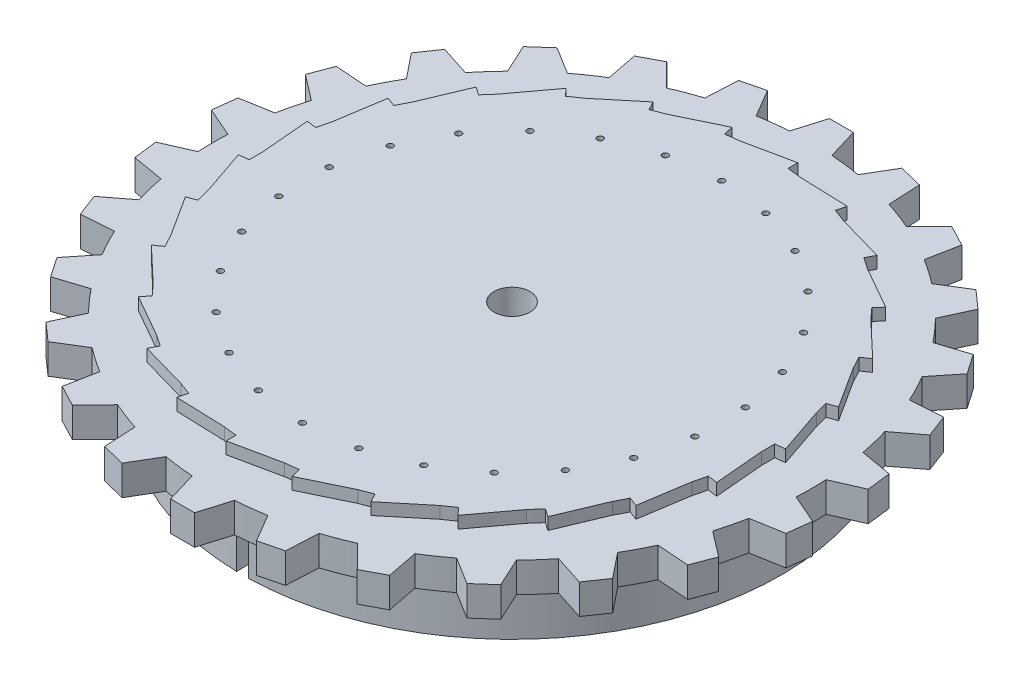
SolidWorks part; units mm, degrees
ref_plane "Front Plane" through (0, 0, 0) normal (0, 0, 1) x (1, 0, 0)
ref_plane "Top Plane" through (0, 0, 0) normal (0, 1, 0) x (1, 0, 0)
ref_plane "Right Plane" through (0, 0, 0) normal (1, 0, 0) x (0, 0, -1)
sketch "Gear sketch" plane through (0, 0, 0) normal (0, 1, 0) x (1, 0, 0)
  line L0 (0, 50) -> (-37.4438, 50) construction
  line L1 (3.5, 50) -> (-3.5, 50) construction
  line L2 (-3.5, 50) -> (-2, 55)
  line L3 (-2, 55) -> (2, 55)
  line L4 (2, 55) -> (3.5, 50)
  line L5 (0, 0) -> (0, 66.1206) construction
  line L6 (8.5675, 49.3847) -> (11.2205, 53.8804)
  line L7 (11.2205, 53.8804) -> (15.1042, 52.9232)
  line L8 (15.1042, 52.9232) -> (15.3641, 47.7095)
  line L9 (15.3641, 47.7095) -> (15.3706, 47.5788)
  line L10 (11.2205, 53.8804) -> (8.501, 49.272)
  line L11 (15.3641, 47.7095) -> (8.5675, 49.3847) construction
  line L12 (20.1371, 45.8993) -> (23.7889, 49.6295)
  line L13 (23.7889, 49.6295) -> (27.3307, 47.7706)
  line L14 (27.3307, 47.7706) -> (26.3353, 42.6463)
  line L15 (26.3353, 42.6463) -> (26.3103, 42.5179)
  line L16 (20.1371, 45.8993) -> (20.0455, 45.8059)
  line L18 (30.5363, 39.7465) -> (34.9747, 42.4943)
  line L19 (34.9747, 42.4943) -> (37.9688, 39.8418)
  line L20 (37.9688, 39.8418) -> (35.7759, 35.1046)
  line L21 (35.7759, 35.1046) -> (35.721, 34.9859)
  line L22 (30.5363, 39.7465) -> (30.4251, 39.6776)
  line L24 (39.161, 31.2837) -> (44.128, 32.8895)
  line L25 (44.128, 32.8895) -> (46.4002, 29.5976)
  line L26 (46.4002, 29.5976) -> (43.1374, 25.5228)
  line L27 (43.1374, 25.5228) -> (43.0557, 25.4207)
  line L28 (39.161, 31.2837) -> (39.0365, 31.2434)
  line L30 (45.5097, 21.0028) -> (50.7167, 21.3733)
  line L31 (50.7167, 21.3733) -> (52.1351, 17.6332)
  line L32 (52.1351, 17.6332) -> (47.9919, 14.4577)
  line L33 (47.9919, 14.4577) -> (47.8881, 14.3781)
  line L34 (45.5097, 21.0028) -> (45.3792, 20.9935)
  line L36 (49.2136, 9.5013) -> (54.3579, 8.6149)
  line L37 (54.3579, 8.6149) -> (54.8401, 4.6441)
  line L38 (54.8401, 4.6441) -> (50.0573, 2.5524)
  line L39 (50.0573, 2.5524) -> (49.9375, 2.4999)
  line L40 (49.2136, 9.5013) -> (49.0846, 9.5235)
  line L42 (50.0573, -2.5524) -> (54.8401, -4.6441)
  line L43 (54.8401, -4.6441) -> (54.3579, -8.6149)
  line L44 (54.3579, -8.6149) -> (49.2136, -9.5013)
  line L45 (49.2136, -9.5013) -> (49.0846, -9.5235)
  line L46 (50.0573, -2.5524) -> (49.9375, -2.4999)
  line L47 (49.2136, -9.5013) -> (50.0573, -2.5524) construction
  line L48 (47.9919, -14.4577) -> (52.1351, -17.6332)
  line L49 (52.1351, -17.6332) -> (50.7167, -21.3733)
  line L50 (50.7167, -21.3733) -> (45.5097, -21.0028)
  line L51 (45.5097, -21.0028) -> (45.3792, -20.9935)
  line L52 (47.9919, -14.4577) -> (47.8881, -14.3781)
  line L54 (43.1374, -25.5228) -> (46.4002, -29.5976)
  line L55 (46.4002, -29.5976) -> (44.128, -32.8895)
  line L56 (44.128, -32.8895) -> (39.161, -31.2837)
  line L57 (39.161, -31.2837) -> (39.0365, -31.2434)
  line L58 (43.1374, -25.5228) -> (43.0557, -25.4207)
  line L60 (35.7759, -35.1046) -> (37.9688, -39.8418)
  line L61 (37.9688, -39.8418) -> (34.9747, -42.4943)
  line L62 (34.9747, -42.4943) -> (30.5363, -39.7465)
  line L63 (30.5363, -39.7465) -> (30.4251, -39.6776)
  line L64 (35.7759, -35.1046) -> (35.721, -34.9859)
  line L66 (26.3353, -42.6463) -> (27.3307, -47.7706)
  line L67 (27.3307, -47.7706) -> (23.7889, -49.6295)
  line L68 (23.7889, -49.6295) -> (20.1371, -45.8993)
  line L69 (20.1371, -45.8993) -> (20.0455, -45.8059)
  line L70 (26.3353, -42.6463) -> (26.3103, -42.5179)
  line L72 (15.3641, -47.7095) -> (15.1042, -52.9232)
  line L73 (15.1042, -52.9232) -> (11.2205, -53.8804)
  line L74 (11.2205, -53.8804) -> (8.5675, -49.3847)
  line L75 (8.5675, -49.3847) -> (8.501, -49.272)
  line L76 (15.3641, -47.7095) -> (15.3706, -47.5788)
  line L78 (3.5, -50) -> (2, -55)
  line L79 (2, -55) -> (-2, -55)
  line L80 (-2, -55) -> (-3.5, -50)
  line L81 (3.5, 50) -> (3.5376, 49.8747)
  line L82 (-3.5, 50) -> (-3.5376, 49.8747)
  line L83 (-3.5, -50) -> (-3.5376, -49.8747)
  line L84 (3.5, -50) -> (3.5376, -49.8747)
  line L86 (-8.5675, -49.3847) -> (-11.2205, -53.8804)
  line L87 (-11.2205, -53.8804) -> (-15.1042, -52.9232)
  line L88 (-15.1042, -52.9232) -> (-15.3641, -47.7095)
  line L89 (-15.3641, -47.7095) -> (-15.3706, -47.5788)
  line L90 (-8.5675, -49.3847) -> (-8.501, -49.272)
  line L92 (-20.1371, -45.8993) -> (-23.7889, -49.6295)
  line L93 (-23.7889, -49.6295) -> (-27.3307, -47.7706)
  line L94 (-27.3307, -47.7706) -> (-26.3353, -42.6463)
  line L95 (-26.3353, -42.6463) -> (-26.3103, -42.5179)
  line L96 (-20.1371, -45.8993) -> (-20.0455, -45.8059)
  line L98 (-30.5363, -39.7465) -> (-34.9747, -42.4943)
  line L99 (-34.9747, -42.4943) -> (-37.9688, -39.8418)
  line L100 (-37.9688, -39.8418) -> (-35.7759, -35.1046)
  line L101 (-35.7759, -35.1046) -> (-35.721, -34.9859)
  line L102 (-30.5363, -39.7465) -> (-30.4251, -39.6776)
  line L104 (-39.161, -31.2837) -> (-44.128, -32.8895)
  line L105 (-44.128, -32.8895) -> (-46.4002, -29.5976)
  line L106 (-46.4002, -29.5976) -> (-43.1374, -25.5228)
  line L107 (-43.1374, -25.5228) -> (-43.0557, -25.4207)
  line L108 (-39.161, -31.2837) -> (-39.0365, -31.2434)
  line L110 (-45.5097, -21.0028) -> (-50.7167, -21.3733)
  line L111 (-50.7167, -21.3733) -> (-52.1351, -17.6332)
  line L112 (-52.1351, -17.6332) -> (-47.9919, -14.4577)
  line L113 (-47.9919, -14.4577) -> (-47.8881, -14.3781)
  line L114 (-45.5097, -21.0028) -> (-45.3792, -20.9935)
  line L116 (-49.2136, -9.5013) -> (-54.3579, -8.6149)
  line L117 (-54.3579, -8.6149) -> (-54.8401, -4.6441)
  line L118 (-54.8401, -4.6441) -> (-50.0573, -2.5524)
  line L119 (-50.0573, -2.5524) -> (-49.9375, -2.4999)
  line L120 (-49.2136, -9.5013) -> (-49.0846, -9.5235)
  line L122 (-50.0573, 2.5524) -> (-54.8401, 4.6441)
  line L123 (-54.8401, 4.6441) -> (-54.3579, 8.6149)
  line L124 (-54.3579, 8.6149) -> (-49.2136, 9.5013)
  line L125 (-49.2136, 9.5013) -> (-49.0846, 9.5235)
  line L126 (-50.0573, 2.5524) -> (-49.9375, 2.4999)
  line L128 (-47.9919, 14.4577) -> (-52.1351, 17.6332)
  line L129 (-52.1351, 17.6332) -> (-50.7167, 21.3733)
  line L130 (-50.7167, 21.3733) -> (-45.5097, 21.0028)
  line L131 (-45.5097, 21.0028) -> (-45.3792, 20.9935)
  line L132 (-47.9919, 14.4577) -> (-47.8881, 14.3781)
  line L134 (-43.1374, 25.5228) -> (-46.4002, 29.5976)
  line L135 (-46.4002, 29.5976) -> (-44.128, 32.8895)
  line L136 (-44.128, 32.8895) -> (-39.161, 31.2837)
  line L137 (-39.161, 31.2837) -> (-39.0365, 31.2434)
  line L138 (-43.1374, 25.5228) -> (-43.0557, 25.4207)
  line L140 (-35.7759, 35.1046) -> (-37.9688, 39.8418)
  line L141 (-37.9688, 39.8418) -> (-34.9747, 42.4943)
  line L142 (-34.9747, 42.4943) -> (-30.5363, 39.7465)
  line L143 (-30.5363, 39.7465) -> (-30.4251, 39.6776)
  line L144 (-35.7759, 35.1046) -> (-35.721, 34.9859)
  line L145 (-30.5363, 39.7465) -> (-35.7759, 35.1046) construction
  line L146 (-26.3353, 42.6463) -> (-27.3307, 47.7706)
  line L147 (-27.3307, 47.7706) -> (-23.7889, 49.6295)
  line L148 (-23.7889, 49.6295) -> (-20.1371, 45.8993)
  line L149 (-20.1371, 45.8993) -> (-20.0455, 45.8059)
  line L150 (-26.3353, 42.6463) -> (-26.3103, 42.5179)
  line L151 (-20.1371, 45.8993) -> (-23.2362, 44.2728) construction
  line L152 (-15.3641, 47.7095) -> (-15.1042, 52.9232)
  line L153 (-15.1042, 52.9232) -> (-11.2205, 53.8804)
  line L154 (-11.2205, 53.8804) -> (-8.5675, 49.3847)
  line L155 (-8.5675, 49.3847) -> (-8.501, 49.272)
  line L156 (-15.3641, 47.7095) -> (-15.3706, 47.5788)
  line L159 (49.6354, 6.0268) -> (49.2136, 9.5013) construction
  line L160 (47.9919, 14.4577) -> (45.5097, 21.0028) construction
  line L161 (43.1374, 25.5228) -> (39.161, 31.2837) construction
  line L162 (35.7759, 35.1046) -> (30.5363, 39.7465) construction
  line L163 (26.3353, 42.6463) -> (20.1371, 45.8993) construction
  line L164 (45.5097, -21.0028) -> (47.9919, -14.4577) construction
  line L165 (39.161, -31.2837) -> (41.1492, -28.4032) construction
  line L166 (30.5363, -39.7465) -> (35.7759, -35.1046) construction
  line L167 (20.1371, -45.8993) -> (23.2362, -44.2728) construction
  line L168 (11.9658, -48.5471) -> (15.3641, -47.7095) construction
  line L169 (-3.5, -50) -> (0, -50) construction
  line L170 (-15.3641, -47.7095) -> (-8.5675, -49.3847) construction
  line L171 (-26.3353, -42.6463) -> (-23.2362, -44.2728) construction
  line L172 (-33.1561, -37.4255) -> (-30.5363, -39.7465) construction
  line L173 (-41.1492, -28.4032) -> (-39.161, -31.2837) construction
  line L174 (-46.7508, -17.7302) -> (-45.5097, -21.0028) construction
  line L175 (-49.6354, -6.0268) -> (-49.2136, -9.5013) construction
  line L176 (-49.2136, 9.5013) -> (-49.6354, 6.0268) construction
  line L177 (-45.5097, 21.0028) -> (-46.7508, 17.7302) construction
  line L178 (-39.161, 31.2837) -> (-41.1492, 28.4032) construction
  line L179 (-8.5675, 49.3847) -> (-15.3641, 47.7095) construction
  arc A0 (-3.5376, 49.8747) -> (-8.501, 49.272) centre (0, 0) ccw
  arc A1 (8.501, 49.272) -> (3.5376, 49.8747) centre (0, 0) ccw
  arc A2 (20.0455, 45.8059) -> (15.3706, 47.5788) centre (0, 0) ccw
  arc A3 (30.4251, 39.6776) -> (26.3103, 42.5179) centre (0, 0) ccw
  arc A4 (39.0365, 31.2434) -> (35.721, 34.9859) centre (0, 0) ccw
  arc A5 (45.3792, 20.9935) -> (43.0557, 25.4207) centre (0, 0) ccw
  arc A6 (49.9375, -2.4999) -> (49.9375, 2.4999) centre (0, 0) ccw
  arc A7 (49.0846, 9.5235) -> (47.8881, 14.3781) centre (0, 0) ccw
  arc A8 (47.8881, -14.3781) -> (49.0846, -9.5235) centre (0, 0) ccw
  arc A9 (43.0557, -25.4207) -> (45.3792, -20.9935) centre (0, 0) ccw
  arc A10 (35.721, -34.9859) -> (39.0365, -31.2434) centre (0, 0) ccw
  arc A11 (26.3103, -42.5179) -> (30.4251, -39.6776) centre (0, 0) ccw
  arc A12 (15.3706, -47.5788) -> (20.0455, -45.8059) centre (0, 0) ccw
  arc A13 (3.5376, -49.8747) -> (8.501, -49.272) centre (0, 0) ccw
  arc A14 (-8.501, -49.272) -> (-3.5376, -49.8747) centre (0, 0) ccw
  arc A15 (-20.0455, -45.8059) -> (-15.3706, -47.5788) centre (0, 0) ccw
  arc A16 (-30.4251, -39.6776) -> (-26.3103, -42.5179) centre (0, 0) ccw
  arc A17 (-39.0365, -31.2434) -> (-35.721, -34.9859) centre (0, 0) ccw
  arc A18 (-45.3792, -20.9935) -> (-43.0557, -25.4207) centre (0, 0) ccw
  arc A19 (-49.0846, -9.5235) -> (-47.8881, -14.3781) centre (0, 0) ccw
  arc A20 (-49.9375, 2.4999) -> (-49.9375, -2.4999) centre (0, 0) ccw
  arc A21 (-47.8881, 14.3781) -> (-49.0846, 9.5235) centre (0, 0) ccw
  arc A22 (-43.0557, 25.4207) -> (-45.3792, 20.9935) centre (0, 0) ccw
  arc A23 (-26.3103, 42.5179) -> (-30.4251, 39.6776) centre (0, 0) ccw
  arc A24 (-15.3706, 47.5788) -> (-20.0455, 45.8059) centre (0, 0) ccw
  arc A25 (-35.721, 34.9859) -> (-39.0365, 31.2434) centre (0, 0) ccw
  point P7 (0, 49.8773)
  point P8 (50, 0)
  point P12 (0, -50)
  point P13 (-50, 0)
  point P14 (0.3591, 49.9987)
  point P20 (11.9364, 48.428)
  point P23 (12.3142, 48.4599)
  point P28 (23.1792, 44.1642)
  point P31 (23.5535, 44.1048)
  point P36 (33.0748, 37.3337)
  point P39 (33.4241, 37.1864)
  point P44 (41.0483, 28.3336)
  point P47 (41.3521, 28.107)
  point P52 (46.6361, 17.6868)
  point P55 (46.877, 17.394)
  point P57 (0, 0)
  point P61 (49.5137, 6.0121)
  point P64 (49.6775, 5.6702)
  point P69 (49.5137, -6.0121)
  point P72 (49.5909, -6.3832)
  point P77 (46.6361, -17.6868)
  point P80 (46.6223, -18.0656)
  point P85 (41.0483, -28.3336)
  point P88 (40.9441, -28.6981)
  point P93 (33.0748, -37.3337)
  point P96 (32.8865, -37.6627)
  point P101 (23.1792, -44.1642)
  point P104 (22.9176, -44.4386)
  point P109 (11.9364, -48.428)
  point P112 (11.6168, -48.6318)
  point P117 (0, 0)
  point P118 (0, -49.8773)
  point P122 (-0.3591, -49.9987)
  point P127 (-11.9364, -48.428)
  point P130 (-12.3142, -48.4599)
  point P135 (-23.1792, -44.1642)
  point P138 (-23.5535, -44.1048)
  point P143 (-33.0748, -37.3337)
  point P146 (-33.4241, -37.1864)
  point P151 (-41.0483, -28.3336)
  point P154 (-41.3521, -28.107)
  point P159 (-46.6361, -17.6868)
  point P162 (-46.877, -17.394)
  point P167 (-49.5137, -6.0121)
  point P170 (-49.6775, -5.6702)
  point P175 (-49.5137, 6.0121)
  point P178 (-49.5909, 6.3832)
  point P183 (-46.6361, 17.6868)
  point P186 (-46.6223, 18.0656)
  point P191 (-41.0483, 28.3336)
  point P194 (-40.9441, 28.6981)
  point P199 (-33.0748, 37.3337)
  point P202 (-32.8865, 37.6627)
  point P207 (-23.1792, 44.1642)
  point P210 (-22.9176, 44.4386)
  point P215 (-11.9364, 48.428)
  point P218 (-11.6168, 48.6318)
  point P221 (0, 0)
  dimension "D1" = 100
  dimension "D2" = 4
  dimension "D3" = 7
  dimension "D4" = 5
  dimension "D5" = 26
extrude "Gear Extrude" add sketch "Gear sketch" along normal blind 5 contours L7 L8 L9 A2 L16 L12 L13 L14 L15 A3 L22 L18 L19 L20 L21 A4 L28 L24 L25 L26 L27 A5 L34 L30 L31 L32 L33 A7 L40 L36 L37 L38 L39 A6 L46 L42 L43 L44 L45 A8 L52 L48 L49 L50 L51 A9 L58 L54 L55 L56 L57 A10 L64 L60 L61 L62 L63 A11 L70 L66 L67 L68 L69 A12 L76 L72 L73 L74 L75 A13 L84 L78 L79 L80 L83 A14 L90 L86 L87 L88 L89 A15 L96 L92 L93 L94 L95 A16 L102 L98 L99 L100 L101 A17 L108 L104 L105 L106 L107 A18 L114 L110 L111 L112 L113 A19 L120 L116 L117 L118 L119 A20 L126 L122 L123 L124 L125 A21 L132 L128 L129 L130 L131 A22 L138 L134 L135 L136 L137 A25 L144 L140 L141 L142 L143 A23 L150 L146 L147 L148 L149 A24 L156 L152 L153 L154 L155 A0 L82 L2 L3 L4 L81 A1 L10
sketch "Center hole sketch" plane through (0, 0, 0) normal (0, -1, 0) x (-1, 0, 0)
  line L0 (0, 0) -> (0, -82.0366) construction
  line L3 (1, -44.9889) -> (1.016, -42.988)
  line L4 (-1, -44.9889) -> (-0.984, -42.9887)
  arc A0 (1, -44.9889) -> (-1, -44.9889) centre (0, 0) ccw
  arc A1 (1.016, -42.988) -> (-0.984, -42.9887) centre (0, 0) ccw
  dimension "D1" = 90
  dimension "D2" = 2
  dimension "D3" = 2
  dimension "D4" = 2
extrude "Center rotator" add sketch "Center hole sketch" along normal blind 10
sketch "Sketch7" plane through (0, 5, 0) normal (0, -1, 0) x (1, 0, 0)
  line L0 (0, 35) -> (4.0215, 35) construction
  line L1 (4.0215, 35) -> (-4.0215, 35) construction
  line L2 (0, 35) -> (0, 47.5839) construction
  line L3 (-3.7482, 43.9753) -> (4.3006, 42.2818)
  line L4 (-3.7482, 43.9753) -> (-3.7482, 42.3344)
  line L5 (6.8847, 43.5944) -> (14.2944, 40.024)
  line L6 (6.8847, 43.5944) -> (6.492, 42.0012)
  line L7 (17.1175, 40.6801) -> (23.4574, 35.4401)
  line L8 (17.1175, 40.6801) -> (16.3549, 39.2271)
  line L9 (26.3555, 35.4015) -> (31.2571, 28.7966)
  line L10 (26.3555, 35.4015) -> (25.2673, 34.1733)
  line L11 (34.0617, 28.0655) -> (37.2403, 20.4795)
  line L12 (34.0617, 28.0655) -> (32.7113, 27.1334)
  line L13 (39.7885, 19.0985) -> (41.0592, 10.9722)
  line L14 (39.7885, 19.0985) -> (38.2542, 18.5166)
  line L15 (43.2029, 9.0215) -> (42.4919, 0.8273)
  line L16 (43.2029, 9.0215) -> (41.5739, 8.8237)
  line L17 (44.1065, -1.5798) -> (41.4552, -9.3658)
  line L18 (44.1065, -1.5798) -> (42.4775, -1.382)
  line L19 (42.4467, -12.0892) -> (38.0092, -19.0145)
  line L20 (42.4467, -12.0892) -> (40.9125, -11.5074)
  line L21 (38.3202, -21.8961) -> (32.3542, -27.5582)
  line L22 (38.3202, -21.8961) -> (36.9697, -20.964)
  line L23 (31.9666, -30.4305) -> (24.819, -34.5003)
  line L24 (31.9666, -30.4305) -> (30.8785, -29.2022)
  line L25 (23.7552, -37.1963) -> (15.8413, -39.4373)
  line L26 (23.7552, -37.1963) -> (22.9926, -35.7434)
  line L27 (14.1632, -41.8004) -> (5.9431, -42.0824)
  line L28 (14.1632, -41.8004) -> (13.7706, -40.2072)
  line L29 (3.7482, -43.9753) -> (-4.3006, -42.2818)
  line L30 (3.7482, -43.9753) -> (3.7482, -42.3344)
  line L31 (-6.8847, -43.5944) -> (-14.2944, -40.024)
  line L32 (-6.8847, -43.5944) -> (-6.492, -42.0012)
  line L33 (-17.1175, -40.6801) -> (-23.4574, -35.4401)
  line L34 (-17.1175, -40.6801) -> (-16.3549, -39.2271)
  line L35 (-26.3555, -35.4015) -> (-31.2571, -28.7966)
  line L36 (-26.3555, -35.4015) -> (-25.2673, -34.1733)
  line L37 (-34.0617, -28.0655) -> (-37.2403, -20.4795)
  line L38 (-34.0617, -28.0655) -> (-32.7113, -27.1334)
  line L39 (-39.7885, -19.0985) -> (-41.0592, -10.9722)
  line L40 (-39.7885, -19.0985) -> (-38.2542, -18.5166)
  line L41 (-43.2029, -9.0215) -> (-42.4919, -0.8273)
  line L42 (-43.2029, -9.0215) -> (-41.5739, -8.8237)
  line L43 (-44.1065, 1.5798) -> (-41.4552, 9.3658)
  line L44 (-44.1065, 1.5798) -> (-42.4775, 1.382)
  line L45 (-42.4467, 12.0892) -> (-38.0092, 19.0145)
  line L46 (-42.4467, 12.0892) -> (-40.9125, 11.5074)
  line L47 (-38.3202, 21.8961) -> (-32.3542, 27.5582)
  line L48 (-38.3202, 21.8961) -> (-36.9697, 20.964)
  line L49 (-31.9666, 30.4305) -> (-24.819, 34.5003)
  line L50 (-31.9666, 30.4305) -> (-30.8785, 29.2022)
  line L51 (-23.7552, 37.1963) -> (-15.8413, 39.4373)
  line L52 (-23.7552, 37.1963) -> (-22.9926, 35.7434)
  line L53 (-14.1632, 41.8004) -> (-5.9431, 42.0824)
  line L54 (-14.1632, 41.8004) -> (-13.7706, 40.2072)
  arc A0 (-13.7706, 40.2072) -> (-15.8413, 39.4373) centre (0, 0) ccw
  arc A1 (-22.9926, 35.7434) -> (-24.819, 34.5003) centre (0, 0) ccw
  arc A2 (-30.8785, 29.2022) -> (-32.3542, 27.5582) centre (0, 0) ccw
  arc A3 (-36.9697, 20.964) -> (-38.0092, 19.0145) centre (0, 0) ccw
  arc A4 (-3.7482, 42.3344) -> (-5.9431, 42.0824) centre (0, 0) ccw
  arc A5 (6.492, 42.0012) -> (4.3006, 42.2818) centre (0, 0) ccw
  arc A6 (16.3549, 39.2271) -> (14.2944, 40.024) centre (0, 0) ccw
  arc A7 (25.2673, 34.1733) -> (23.4574, 35.4401) centre (0, 0) ccw
  arc A8 (-40.9125, 11.5074) -> (-41.4552, 9.3658) centre (0, 0) ccw
  arc A9 (-42.4775, 1.382) -> (-42.4919, -0.8273) centre (0, 0) ccw
  arc A10 (-41.5739, -8.8237) -> (-41.0592, -10.9722) centre (0, 0) ccw
  arc A11 (-38.2542, -18.5166) -> (-37.2403, -20.4795) centre (0, 0) ccw
  arc A12 (-25.2673, -34.1733) -> (-23.4574, -35.4401) centre (0, 0) ccw
  arc A13 (-32.7113, -27.1334) -> (-31.2571, -28.7966) centre (0, 0) ccw
  arc A14 (-16.3549, -39.2271) -> (-14.2944, -40.024) centre (0, 0) ccw
  arc A15 (-6.492, -42.0012) -> (-4.3006, -42.2818) centre (0, 0) ccw
  arc A16 (3.7482, -42.3344) -> (5.9431, -42.0824) centre (0, 0) ccw
  arc A17 (13.7706, -40.2072) -> (15.8413, -39.4373) centre (0, 0) ccw
  arc A18 (22.9926, -35.7434) -> (24.819, -34.5003) centre (0, 0) ccw
  arc A19 (30.8785, -29.2022) -> (32.3542, -27.5582) centre (0, 0) ccw
  arc A20 (36.9697, -20.964) -> (38.0092, -19.0145) centre (0, 0) ccw
  arc A21 (40.9125, -11.5074) -> (41.4552, -9.3658) centre (0, 0) ccw
  arc A22 (42.4775, -1.382) -> (42.4919, 0.8273) centre (0, 0) ccw
  arc A23 (41.5739, 8.8237) -> (41.0592, 10.9722) centre (0, 0) ccw
  arc A24 (38.2542, 18.5166) -> (37.2403, 20.4795) centre (0, 0) ccw
  arc A25 (32.7113, 27.1334) -> (31.2571, 28.7966) centre (0, 0) ccw
  point P89 (0, 0)
  dimension "D1" = 85
  dimension "D2" = 26
extrude "Boss-Extrude3" add sketch "Sketch7" against normal blind 2
sketch "Sketch6" plane through (0, 7, 0) normal (0, -1, 0) x (1, 0, 0)
  line L0 (0, 0) -> (0, -67.5176) construction
  circle A0 centre (0, 0) radius 3
  circle A1 centre (0, -35) radius 0.5
  circle A3 centre (-8.376, -33.983) radius 0.5
  circle A5 centre (-16.2653, -30.991) radius 0.5
  circle A7 centre (-23.2093, -26.1979) radius 0.5
  circle A9 centre (-28.8044, -19.8823) radius 0.5
  circle A11 centre (-32.7256, -12.4112) radius 0.5
  circle A13 centre (-34.7448, -4.2188) radius 0.5
  circle A15 centre (-34.7448, 4.2188) radius 0.5
  circle A17 centre (-32.7256, 12.4112) radius 0.5
  circle A19 centre (-28.8044, 19.8823) radius 0.5
  circle A21 centre (-23.2093, 26.1979) radius 0.5
  circle A23 centre (-16.2653, 30.991) radius 0.5
  circle A25 centre (-8.376, 33.983) radius 0.5
  circle A27 centre (0, 35) radius 0.5
  circle A29 centre (8.376, 33.983) radius 0.5
  circle A31 centre (16.2653, 30.991) radius 0.5
  circle A33 centre (23.2093, 26.1979) radius 0.5
  circle A35 centre (28.8044, 19.8823) radius 0.5
  circle A37 centre (32.7256, 12.4112) radius 0.5
  circle A39 centre (34.7448, 4.2188) radius 0.5
  circle A41 centre (34.7448, -4.2188) radius 0.5
  circle A43 centre (32.7256, -12.4112) radius 0.5
  circle A45 centre (28.8044, -19.8823) radius 0.5
  circle A47 centre (23.2093, -26.1979) radius 0.5
  circle A49 centre (16.2653, -30.991) radius 0.5
  circle A51 centre (8.376, -33.983) radius 0.5
  dimension "D1" = 6
  dimension "D4" = 26
extrude "Cut-Extrude3" cut sketch "Sketch6" along normal through all
sketch "Sketch8" plane through (0, 0, 0) normal (0, -1, 0) x (1, 0, 0)
  line L0 (2, -55) -> (3.5376, -49.8747)
  line L1 (3.5376, -49.8747) -> (-3.5376, -49.8747)
  line L2 (-3.5376, -49.8747) -> (-2, -55)
  line L3 (-2, -55) -> (2, -55)
extrude "Boss-Extrude4" add sketch "Sketch8" along normal blind 5
